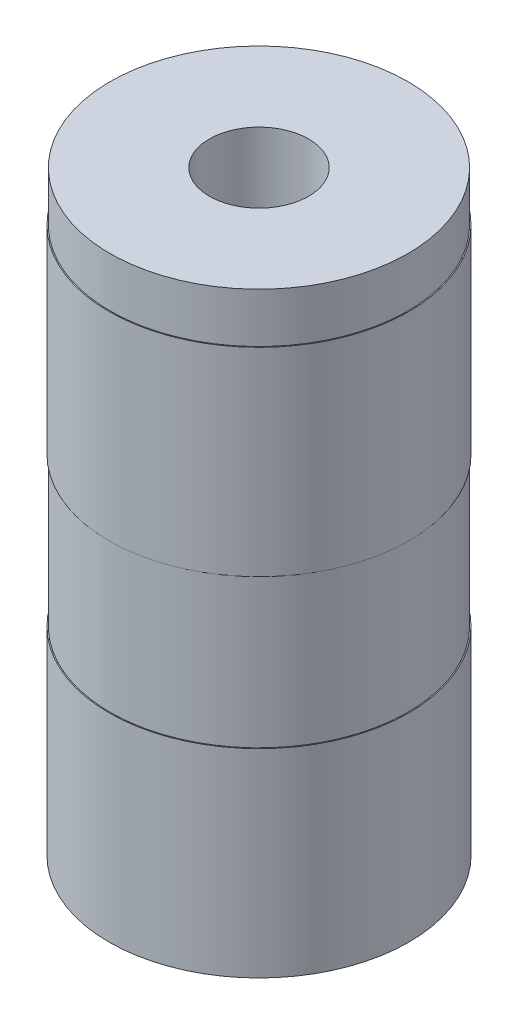
SolidWorks part; units mm, degrees
material "Polyurethane Foam Flexible"
ref_plane "Front" through (0, 0, 0) normal (0, 0, 1) x (1, 0, 0)
ref_plane "Top" through (0, 0, 0) normal (0, 1, 0) x (1, 0, 0)
ref_plane "Right" through (0, 0, 0) normal (1, 0, 0) x (0, 0, -1)
sketch "Sketch1" plane through (0, 0, 0) normal (0, 0, 1) x (1, 0, 0)
  line L0 (0, 0) -> (0, 63.9032) construction
  line L1 (15.1, 55) -> (15, 55)
  line L2 (5, 0) -> (15, 0)
  line L3 (5, 0) -> (5, 60)
  line L4 (5, 60) -> (15, 60)
  line L5 (15, 0) -> (15, 60)
  line L6 (15.1, 55) -> (15.1, 35)
  line L7 (15.1, 35) -> (15, 35)
  line L8 (15, 20) -> (15.1, 20)
  line L9 (15.1, 20) -> (15.1, 0)
  line L10 (15.1, 0) -> (15, 0)
  dimension "D1" = 5
  dimension "D2" = 60
  dimension "D3" = 10
  dimension "D4" = 0.1
  dimension "D5" = 20
  dimension "D6" = 5
  dimension "D7" = 20
  dimension "D8" = 15
revolve "Revolve1" add sketch "Sketch1" angle 360 about L0
